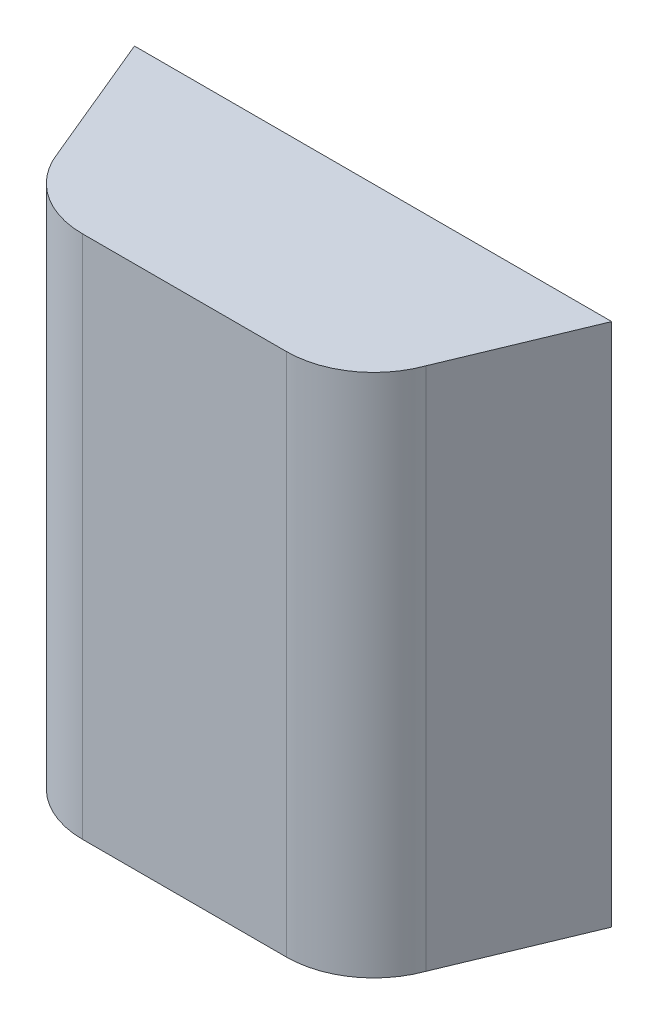
SolidWorks part; units mm, degrees
ref_plane "Front Plane" through (0, 0, 0) normal (0, 0, 1) x (1, 0, 0)
ref_plane "Top Plane" through (0, 0, 0) normal (0, 1, 0) x (1, 0, 0)
ref_plane "Right Plane" through (0, 0, 0) normal (1, 0, 0) x (0, 0, -1)
sketch "Sketch1" plane through (0, 0, 0) normal (0, 1, 0) x (1, 0, 0)
  line L1 (35, 0) -> (-35, 0)
  line L3 (-81.9087, 64.7394) -> (-63.1908, 19.7394)
  line L4 (-81.9087, 64.7394) -> (81.9087, 64.7394)
  line L5 (81.9087, 64.7394) -> (63.1908, 19.7394)
  arc A0 (-63.1908, 19.7394) -> (-35, 0) centre (-35, 30) ccw
  arc A1 (63.1908, 19.7394) -> (35, 0) centre (35, 30) cw
  point P9 (0, 27.0479)
  point P10 (0, 0)
  point P13 (0, 64.7394)
  point P14 (0, 0)
  dimension "D2" = 45
  dimension "D1" = 35
extrude "Boss-Extrude1" add sketch "Sketch1" along normal blind 180
sketch "Sketch4" plane through (0, 0, 0) normal (0, -1, 0) x (1, 0, 0)
  line L1 (81.9087, -64.7394) -> (-81.9087, -64.7394) construction
  line L5 (-78.9087, -64.7394) -> (78.9087, -64.7394)
  line L6 (-35, -3) -> (35, -3)
  line L8 (-60.7889, -21.7644) -> (-78.9087, -64.7394)
  line L9 (60.7889, -21.7644) -> (78.9087, -64.7394)
  spline S0 degree 2 poles (-35, -3) (-54.7695, -6.8423) (-60.7889, -21.7644) knots 0 0 0 1 1 1
  spline S1 degree 2 poles (35, -3) (54.7695, -6.8423) (60.7889, -21.7644) knots 0 0 0 1 1 1
  point P6 (0, -64.7394)
  point P11 (0, -3)
extrude "Cut-Extrude1" cut sketch "Sketch4" against normal blind 176
